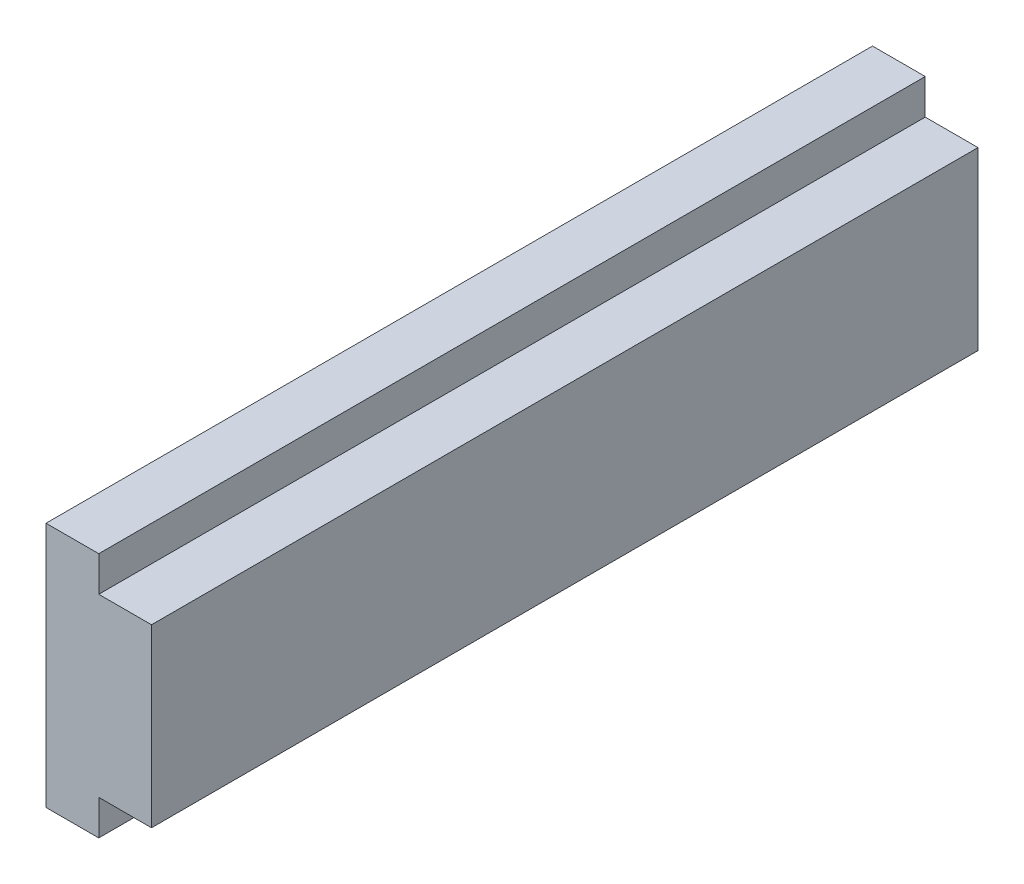
SolidWorks part; units mm, degrees
ref_plane "정면" through (0, 0, 0) normal (0, 0, 1) x (1, 0, 0)
ref_plane "윗면" through (0, 0, 0) normal (0, 1, 0) x (1, 0, 0)
ref_plane "우측면" through (0, 0, 0) normal (1, 0, 0) x (0, 0, -1)
sketch "스케치1" plane through (0, 0, 0) normal (0, 0, 1) x (1, 0, 0)
  line L1 (0, 0) -> (3, 0)
  line L2 (0, 0) -> (0, 14)
  line L3 (0, 14) -> (3, 14)
  line L4 (3, 0) -> (3, 14)
  line L5 (3, 12) -> (6, 12)
  line L6 (3, 12) -> (3, 2)
  line L7 (3, 2) -> (6, 2)
  line L8 (6, 12) -> (6, 2)
  dimension "D1" = 2
  dimension "D2" = 3
  dimension "D3" = 2
  dimension "D4" = 3
  dimension "D5" = 14
extrude "보스-돌출1" add sketch "스케치1" along normal blind 47 contours L1 L4 L3 L2 | L8 L5 L4 L7
